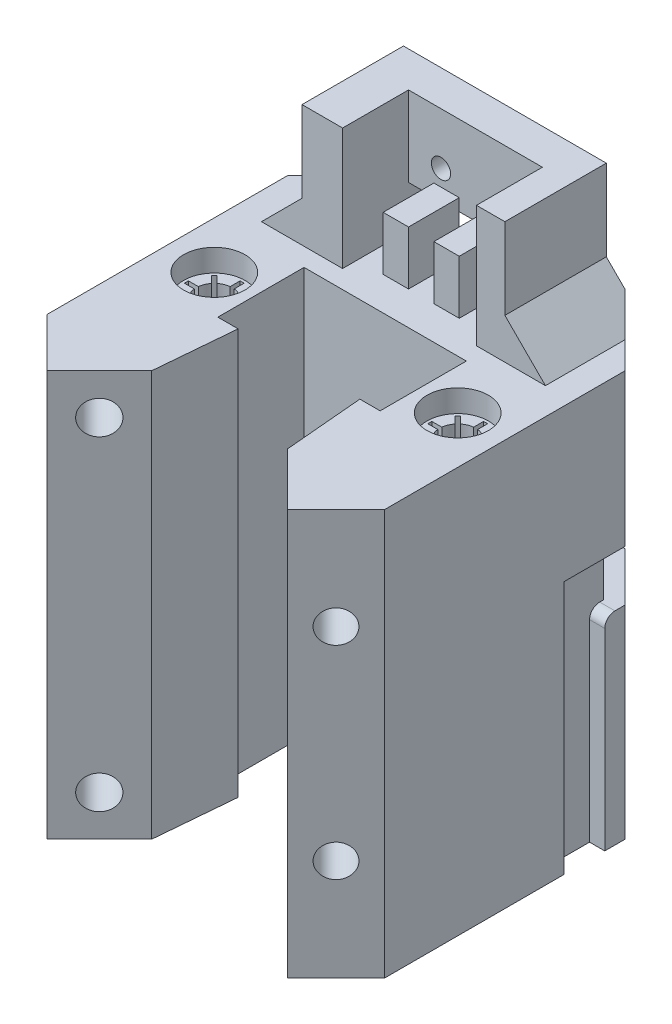
SolidWorks part; units mm, degrees
ref_plane "前视基准面" through (0, 0, 0) normal (0, 0, 1) x (1, 0, 0)
ref_plane "上视基准面" through (0, 0, 0) normal (0, 1, 0) x (1, 0, 0)
ref_plane "右视基准面" through (0, 0, 0) normal (1, 0, 0) x (0, 0, -1)
sketch "草图1" plane through (0, 0, 0) normal (0, 1, 0) x (1, 0, 0)
  line L0 (0, 0) -> (31, 0) construction
  line L1 (0, 0) -> (24.3952, -24.3952) construction
  line L2 (-31, 12) -> (-31, -12) construction
  line L3 (-32.8805, 15.9099) -> (-15.9099, 32.8805) construction
  line L4 (-24.3952, 24.3952) -> (0, 0) construction
  line L5 (-31, 0) -> (0, 0) construction
  line L6 (-43, 22.7609) -> (-43, -22.7609) construction
  line L7 (-43, 22.7609) -> (-22.7609, 43) construction
  line L8 (-24.3952, 24.3952) -> (-32.8805, 32.8805) construction
  line L9 (-31, 0) -> (-43, 0) construction
  line L10 (22.7609, 43) -> (43, 22.7609) construction
  line L11 (22.7609, 43) -> (-22.7609, 43) construction
  line L12 (43, -22.7609) -> (22.7609, -43) construction
  line L13 (43, -22.7609) -> (43, 22.7609) construction
  line L14 (-22.7609, -43) -> (-43, -22.7609) construction
  line L15 (-22.7609, -43) -> (22.7609, -43) construction
  line L16 (24.0036, 46) -> (-24.0036, 46) construction
  line L17 (-46, 24.0036) -> (-24.0036, 46) construction
  line L18 (-46, 24.0036) -> (-46, -24.0036) construction
  line L19 (-24.0036, -46) -> (-46, -24.0036) construction
  line L20 (-24.0036, -46) -> (24.0036, -46) construction
  line L21 (46, -24.0036) -> (24.0036, -46) construction
  line L22 (46, -24.0036) -> (46, 24.0036) construction
  line L23 (24.0036, 46) -> (46, 24.0036) construction
  line L24 (11.8464, 16.65) -> (-11.8464, 16.65)
  line L25 (-16.65, 11.8464) -> (-11.8464, 16.65)
  line L26 (-16.65, 11.8464) -> (-16.65, -11.8464)
  line L27 (-11.8464, -16.65) -> (-16.65, -11.8464)
  line L28 (-11.8464, -16.65) -> (11.8464, -16.65)
  line L29 (16.65, -11.8464) -> (11.8464, -16.65)
  line L30 (16.65, -11.8464) -> (16.65, 11.8464)
  line L31 (11.8464, 16.65) -> (16.65, 11.8464)
  circle A0 centre (0, 0) radius 15 construction
  circle A1 centre (31, 0) radius 12 construction
  circle A2 centre (24.3952, -24.3952) radius 12 construction
  circle A3 centre (0, -31) radius 12 construction
  circle A4 centre (-24.3952, -24.3952) radius 12 construction
  circle A5 centre (-31, 0) radius 12 construction
  circle A6 centre (-24.3952, 24.3952) radius 12 construction
  circle A7 centre (0, 31) radius 12 construction
  circle A8 centre (24.3952, 24.3952) radius 12 construction
  point P22 (0, 0)
  point P41 (0, 0)
  dimension "D1" = 30
  dimension "D2" = 24
  dimension "D3" = 31
  dimension "D4" = 34.5
  dimension "D5" = 45
  dimension "D8" = 3
  dimension "D9" = 26.35
  dimension "D6" = 4
  dimension "D7" = 4
extrude "凸台-拉伸1" add sketch "草图1" along normal blind 40
sketch "草图2" plane through (0, 40, 0) normal (0, 1, 0) x (1, 0, 0)
  line L0 (0, 0) -> (12, 0) construction
  line L1 (0, 0) -> (0, 18.2008) construction
  circle A0 centre (12, 0) radius 1.7
  circle A1 centre (-12, 0) radius 1.7
  dimension "D1" = 3.4
  dimension "D2" = 24
extrude "切除-拉伸1" cut sketch "草图2" against normal through all
sketch "草图3" plane through (0, 40, 0) normal (0, 1, 0) x (1, 0, 0)
  line L0 (0, 0) -> (0, -22.2905) construction
  line L1 (-6, -3.65) -> (6, -3.65)
  line L2 (6, -3.65) -> (6.6859, -11.4895)
  line L5 (-11.8464, -16.65) -> (11.8464, -16.65) construction
  line L9 (-6, -3.65) -> (-6.6859, -11.4895)
  line L10 (6.6859, -11.4895) -> (11.8464, -16.65)
  line L11 (11.8464, -16.65) -> (-11.8464, -16.65)
  line L12 (-6.6859, -11.4895) -> (-11.8464, -16.65)
  point P7 (0, -16.65)
  point P12 (0, -16.65)
  point P15 (0, -3.65)
  dimension "D1" = 45
  dimension "D2" = 12
  dimension "D3" = 95
  dimension "D4" = 13
extrude "切除-拉伸2" cut sketch "草图3" against normal through all
sketch "草图4" plane through (0, 40, 0) normal (0, 1, 0) x (1, 0, 0)
  line L0 (0, 0) -> (0, 19.1016) construction
  line L1 (11.8464, 16.65) -> (-11.8464, 16.65) construction
  line L2 (-10, 6.65) -> (10, 6.65)
  line L3 (-10, 6.65) -> (-10, 16.65)
  line L4 (-10, 16.65) -> (10, 16.65)
  line L5 (10, 6.65) -> (10, 16.65)
  line L6 (-10, 6.65) -> (10, 16.65) construction
  line L7 (-10, 16.65) -> (10, 6.65) construction
  line L9 (-6, 6.65) -> (7.2, 6.65)
  line L10 (-6, 6.65) -> (-6, 13.15)
  line L11 (-6, 13.15) -> (7.2, 13.15)
  line L12 (7.2, 6.65) -> (7.2, 13.15)
  point P3 (0, 11.65)
  line M13 (11.8464, 16.65) -> (-11.8464, 16.65)
  dimension "D1" = 20
  dimension "D2" = 10
  dimension "D3" = 3.5
  dimension "D4" = 13.2
  dimension "D5" = 4
extrude "凸台-拉伸2" add sketch "草图4" along normal blind 12 contours L12 L2 L5 L3 L10 L11 M13
sketch "草图5" plane through (0, 40, 0) normal (0, 1, 0) x (1, 0, 0)
  line L0 (0, 0) -> (0, 7.6634) construction
  line L1 (6, -3.65) -> (-6, -3.65) construction
  line L2 (-6, 4.85) -> (6, 4.85)
  line L3 (-6, 4.85) -> (-6, -3.65)
  line L4 (-6, -3.65) -> (6, -3.65)
  line L5 (6, 4.85) -> (6, -3.65)
  line L6 (-6, 4.85) -> (6, -3.65) construction
  line L7 (-6, -3.65) -> (6, 4.85) construction
  point P3 (0, 0.6)
  dimension "D1" = 12
  dimension "D2" = 8.5
extrude "切除-拉伸3" cut sketch "草图5" against normal through all
sketch "草图6" plane through (0, 0, 0) normal (0, -1, 0) x (1, 0, 0)
  line L0 (-6, -13.15) -> (7.2, -13.15) construction
  line L1 (-6, -13.15) -> (7.2, -13.15) construction
  line L2 (-6, -6.65) -> (-6, -13.15) construction
  line L3 (-6, -6.65) -> (-6, -13.15)
  line L4 (7.2, -6.65) -> (7.2, -13.15) construction
  line L5 (7.2, -6.65) -> (7.2, -13.15)
  line L6 (-6, -6.65) -> (-6, -4.85) construction
  line L7 (-6, -4.85) -> (6, -4.85) construction
  line L8 (6, -4.85) -> (7.2, -6.65) construction
  line L9 (-6, -6.65) -> (7.2, -6.65)
  line L10 (-6, -13.15) -> (-6, -16.65)
  line L11 (11.8464, -16.65) -> (-11.8464, -16.65) construction
  line L12 (-6, -16.65) -> (7.2, -16.65)
  line L13 (7.2, -16.65) -> (7.2, -13.15)
extrude "切除-拉伸4" cut sketch "草图6" against normal blind 12
sketch "草图7" plane through (0, 40, 0) normal (0, 1, 0) x (1, 0, 0)
  line L0 (-6, 13.15) -> (7.2, 13.15) construction
  line L1 (4, 13.15) -> (1.5, 13.15)
  line L2 (4, 13.15) -> (4, 8.15)
  line L3 (4, 8.15) -> (1.5, 8.15)
  line L4 (1.5, 13.15) -> (1.5, 8.15)
  line L6 (-1, 13.15) -> (-3.5, 13.15)
  line L7 (-1, 13.15) -> (-1, 8.15)
  line L8 (-1, 8.15) -> (-3.5, 8.15)
  line L9 (-3.5, 13.15) -> (-3.5, 8.15)
  line L10 (-6, 6.65) -> (-6, 13.15) construction
  dimension "D1" = 2.5
  dimension "D2" = 2.5
  dimension "D3" = 2.5
  dimension "D4" = 5
extrude "凸台-拉伸3" add sketch "草图7" along normal blind 5.3
sketch "草图8" plane through (0, 12, 0) normal (0, -1, 0) x (1, 0, 0)
  line L1 (-3.5, -11.65) -> (-1, -11.65)
  line L2 (-3.5, -11.65) -> (-3.5, -6.65)
  line L3 (-3.5, -6.65) -> (-1, -6.65)
  line L4 (-1, -11.65) -> (-1, -6.65)
  line L5 (-6, -6.65) -> (-6, -16.65) construction
  line L6 (1.5, -11.65) -> (4, -11.65)
  line L7 (1.5, -11.65) -> (1.5, -6.65)
  line L8 (1.5, -6.65) -> (4, -6.65)
  line L9 (4, -11.65) -> (4, -6.65)
  line L10 (7.2, -6.65) -> (-6, -6.65) construction
  dimension "D1" = 2.5
  dimension "D2" = 2.5
  dimension "D3" = 2.5
  dimension "D4" = 5
extrude "凸台-拉伸4" add sketch "草图8" along normal blind 5.2
sketch "草图10" plane through (0, 40, 0) normal (0, 1, 0) x (1, 0, 0)
  line L0 (6, 0.6) -> (-6, 0.6) construction
  line L1 (6, -3.65) -> (6, 4.85) construction
  line L2 (-6, 4.85) -> (-6, -3.65) construction
  line L3 (6, 4.85) -> (-6, 4.85) construction
  line L4 (-8, -3.65) -> (8, -3.65)
  line L5 (-8, -3.65) -> (-8, 4.85)
  line L6 (-8, 4.85) -> (8, 4.85)
  line L7 (8, -3.65) -> (8, 4.85)
  line L8 (-8, -3.65) -> (8, 4.85) construction
  line L9 (-8, 4.85) -> (8, -3.65) construction
  line L10 (-8, 0.6) -> (8, 0.6) construction
  point P6 (0, 0.6)
  dimension "D1" = 16
extrude "切除-拉伸5" cut sketch "草图10" against normal through all
sketch "草图11" plane through (0, 0, -13.15) normal (0, 0, 1) x (1, 0, 0)
  line L1 (-6, 52) -> (-6, 40) construction
  line L2 (1.5, 45.3) -> (-6, 45.3)
  line L3 (1.5, 45.3) -> (1.5, 40)
  line L4 (1.5, 40) -> (-6, 40)
  line L5 (-6, 45.3) -> (-6, 40)
  line L6 (-6, 44.1) -> (1.5, 44.1)
  dimension "D1" = 1.2
extrude "切除-拉伸6" cut sketch "草图11" against normal blind 11
sketch "草图15" plane through (0, 0, -16.65) normal (0, 0, -1) x (-1, 0, 0)
  line L0 (-1.5, 6.8) -> (-1.5, 12) construction
  line L1 (-1.5, 6.8) -> (-1.5, 12) construction
  line L2 (6, 12) -> (6, 0) construction
  line L3 (6, 12) -> (6, 0) construction
  line L5 (-1.5, 12) -> (6, 12)
  line L6 (-1.5, 12) -> (-1.5, 17)
  line L7 (-1.5, 17) -> (6, 17)
  line L8 (6, 12) -> (6, 17)
  dimension "D1" = 5
extrude "切除-拉伸10" cut sketch "草图15" against normal up to surface (10 mm away) up to face at (0.3667, 8.2667, -6.65)
sketch "草图12" plane through (0, 40, 0) normal (0, 1, 0) x (1, 0, 0)
  line L0 (-6, 6.65) -> (-6, 16.65) construction
  line L1 (1.5, 16.65) -> (-6, 16.65)
  line L2 (1.5, 16.65) -> (1.5, 15.15)
  line L3 (1.5, 15.15) -> (-6, 15.15)
  line L4 (-6, 16.65) -> (-6, 15.15)
  dimension "D1" = 1.5
extrude "切除-拉伸7" cut sketch "草图12" against normal up to surface (28 mm away) up to face at (4.2333, 12, -11.65)
sketch "草图13" plane through (0, 0, 0) normal (0, -1, 0) x (1, 0, 0)
  line L0 (11.8464, -16.65) -> (1.5, -16.65)
  line L1 (1.5, -16.65) -> (7.2, -16.65) construction
  line L18 (1.5, -16.65) -> (7.2, -16.65) construction
  line L19 (11.8464, -16.65) -> (16.65, -11.8464)
  line L20 (16.65, -11.8464) -> (16.65, -5.8464)
  line L21 (16.65, 11.8464) -> (16.65, -11.8464) construction
  line L22 (15.15, -11.2251) -> (15.15, -5.8464)
  line L23 (11.2251, -15.15) -> (15.15, -11.2251)
  line L24 (11.2251, -15.15) -> (1.5, -15.15)
  line L25 (16.65, -5.8464) -> (15.15, -5.8464)
  line L26 (1.5, -16.65) -> (1.5, -15.15)
  dimension "D1" = 6
  dimension "D2" = 1.5
extrude "切除-拉伸8" cut sketch "草图13" against normal blind 5 from offset 20 offset against normal yes
fillet "圆角2" radius 2 1 edges at (-2.25, 17, -15.15)
sketch "草图16" plane through (0, 40, 0) normal (0, 1, 0) x (1, 0, 0)
  circle A0 centre (12, 0) radius 3.025
  circle A1 centre (-12, 0) radius 3.025
  dimension "D1" = 6.05
extrude "切除-拉伸11" cut sketch "草图16" against normal blind 2.2
sketch "草图19" plane through (0, 37.8, 0) normal (0, 1, 0) x (1, 0, 0)
  circle A0 centre (-12, 0) radius 1.7 construction
  circle A1 centre (-12, 0) radius 1.7 construction
  circle A2 centre (12, 0) radius 1.7 construction
  circle A3 centre (12, 0) radius 1.7 construction
  line B0 (-10.1969, 2.086) -> (-10.8907, 1.3921)
  line B1 (-12.2, 2.75) -> (-12.2, 1.7687)
  line B2 (-12.2, 2.75) -> (-11.8, 2.75)
  line B3 (-11.8, 2.75) -> (-11.8, 1.7687)
  line B4 (-9.914, 1.8031) -> (-10.6079, 1.1093)
  line B5 (-10.1969, 2.086) -> (-9.914, 1.8031)
  line B6 (-9.25, 0.2) -> (-10.2313, 0.2)
  line B7 (-9.25, -0.2) -> (-10.2313, -0.2)
  line B8 (-9.25, 0.2) -> (-9.25, -0.2)
  line B9 (-9.914, -1.8031) -> (-10.6079, -1.1093)
  line B10 (-10.1969, -2.086) -> (-10.8907, -1.3921)
  line B11 (-9.914, -1.8031) -> (-10.1969, -2.086)
  line B12 (-11.8, -2.75) -> (-11.8, -1.7687)
  line B13 (-12.2, -2.75) -> (-12.2, -1.7687)
  line B14 (-11.8, -2.75) -> (-12.2, -2.75)
  line B15 (-13.8031, -2.086) -> (-13.1093, -1.3921)
  line B16 (-14.086, -1.8031) -> (-13.3921, -1.1093)
  line B17 (-13.8031, -2.086) -> (-14.086, -1.8031)
  line B18 (-14.75, -0.2) -> (-13.7687, -0.2)
  line B19 (-14.75, 0.2) -> (-13.7687, 0.2)
  line B20 (-14.75, -0.2) -> (-14.75, 0.2)
  line B21 (-14.086, 1.8031) -> (-13.3921, 1.1093)
  line B22 (-13.8031, 2.086) -> (-13.1093, 1.3921)
  line B23 (-14.086, 1.8031) -> (-13.8031, 2.086)
  arc B24 (-12.2, 1.7687) -> (-13.1093, 1.3921) centre (-12, 0) ccw
  arc B25 (-10.8907, 1.3921) -> (-11.8, 1.7687) centre (-12, 0) ccw
  arc B26 (-10.6079, -1.1093) -> (-10.2313, -0.2) centre (-12, 0) ccw
  arc B27 (-11.8, -1.7687) -> (-10.8907, -1.3921) centre (-12, 0) ccw
  arc B28 (-13.1093, -1.3921) -> (-12.2, -1.7687) centre (-12, 0) ccw
  arc B29 (-13.7687, -0.2) -> (-13.3921, -1.1093) centre (-12, 0) ccw
  arc B30 (-13.3921, 1.1093) -> (-13.7687, 0.2) centre (-12, 0) ccw
  arc B31 (-10.2313, 0.2) -> (-10.6079, 1.1093) centre (-12, 0) ccw
  line B32 (13.8031, 2.086) -> (13.1093, 1.3921)
  line B33 (11.8, 2.75) -> (11.8, 1.7687)
  line B34 (11.8, 2.75) -> (12.2, 2.75)
  line B35 (12.2, 2.75) -> (12.2, 1.7687)
  line B36 (14.086, 1.8031) -> (13.3921, 1.1093)
  line B37 (13.8031, 2.086) -> (14.086, 1.8031)
  line B38 (14.75, 0.2) -> (13.7687, 0.2)
  line B39 (14.75, -0.2) -> (13.7687, -0.2)
  line B40 (14.75, 0.2) -> (14.75, -0.2)
  line B41 (14.086, -1.8031) -> (13.3921, -1.1093)
  line B42 (13.8031, -2.086) -> (13.1093, -1.3921)
  line B43 (14.086, -1.8031) -> (13.8031, -2.086)
  line B44 (12.2, -2.75) -> (12.2, -1.7687)
  line B45 (11.8, -2.75) -> (11.8, -1.7687)
  line B46 (12.2, -2.75) -> (11.8, -2.75)
  line B47 (10.1969, -2.086) -> (10.8907, -1.3921)
  line B48 (9.914, -1.8031) -> (10.6079, -1.1093)
  line B49 (10.1969, -2.086) -> (9.914, -1.8031)
  line B50 (9.25, -0.2) -> (10.2313, -0.2)
  line B51 (9.25, 0.2) -> (10.2313, 0.2)
  line B52 (9.25, -0.2) -> (9.25, 0.2)
  line B53 (9.914, 1.8031) -> (10.6079, 1.1093)
  line B54 (10.1969, 2.086) -> (10.8907, 1.3921)
  line B55 (9.914, 1.8031) -> (10.1969, 2.086)
  arc B56 (11.8, 1.7687) -> (10.8907, 1.3921) centre (12, 0) ccw
  arc B57 (13.1093, 1.3921) -> (12.2, 1.7687) centre (12, 0) ccw
  arc B58 (13.3921, -1.1093) -> (13.7687, -0.2) centre (12, 0) ccw
  arc B59 (12.2, -1.7687) -> (13.1093, -1.3921) centre (12, 0) ccw
  arc B60 (10.8907, -1.3921) -> (11.8, -1.7687) centre (12, 0) ccw
  arc B61 (10.2313, -0.2) -> (10.6079, -1.1093) centre (12, 0) ccw
  arc B62 (10.6079, 1.1093) -> (10.2313, 0.2) centre (12, 0) ccw
  arc B63 (13.7687, 0.2) -> (13.3921, 1.1093) centre (12, 0) ccw
sketch_block_instance "块1-1"
sketch_block "块1" parameters "D1"=3.56, "D2"=0.4, "D3"=2.75
sketch_block_instance "块1-2"
sketch_block "块1" parameters "D1"=3.56, "D2"=0.4, "D3"=2.75
extrude "切除-拉伸13" cut sketch "草图19" against normal blind 2.8
ref_plane "基准面1" through (0, 20, 0) normal (0, 1, 0) x (1, 0, 0)
mirror "镜向1" about plane through (0, 20, 0) normal (0, 1, 0) of "切除-拉伸13", "切除-拉伸11"
sketch "草图21" plane through (-14.2482, 0, 14.2482) normal (-0.7071, 0, 0.7071) x (0.7071, 0, 0.7071)
  line L0 (0, 0) -> (0, 40) construction
  line L2 (0, 20) -> (14.1722, 20) construction
  line L3 (-3.3967, 40) -> (3.3967, 40) construction
  line L4 (-3.3967, 0) -> (3.3967, 0) construction
  circle A0 centre (0, 30) radius 1.6
  circle A2 centre (0, 10) radius 1.6
  point P17 (0, 0)
  dimension "D1" = 3.2
  dimension "D2" = 20
  dimension "D3" = 0
extrude "切除-拉伸14" cut sketch "草图21" against normal blind 5
chamfer "倒角1" [suppressed] distance 1 angle 45
mirror "镜向2" about plane through (0, 0, 0) normal (1, 0, 0) of "切除-拉伸14"
mirror "镜向3" about plane through (0, 0, 0) normal (0, 0, 1) of "镜向2", "切除-拉伸14"
sketch "草图17" plane through (0, 20, 0) normal (0, 1, 0) x (1, 0, 0)
  line L5 (15.15, 5.8464) -> (15.15, 11.2251) construction
  line L6 (16.65, 5.8464) -> (15.15, 5.8464)
  line L7 (16.65, 5.8464) -> (16.65, 9.8464)
  line L8 (16.65, 9.8464) -> (15.15, 9.8464)
  line L9 (15.15, 5.8464) -> (15.15, 9.8464)
  dimension "D1" = 4
extrude "切除-拉伸12" cut sketch "草图17" against normal through all
fillet "圆角3" radius 1 3 edges at (15.9, 20, -9.8464) (1.5, 20, -15.9) (1.5, 25, -15.9)
chamfer "倒角2" distance 4 angle 45 2 edges at (10, 40, -11.65) (-10, 40, -11.65)
sketch "草图22" plane through (0, 0, -13.15) normal (0, 0, 1) x (1, 0, 0)
  line L0 (-2.8, 46.9) -> (3.7, 46.9) construction
  line L1 (-6, 52) -> (-6, 40) construction
  line L2 (-6, 52) -> (7.2, 52) construction
  circle A0 centre (-2.8, 46.9) radius 0.95
  circle A1 centre (3.7, 46.9) radius 0.95
  dimension "D1" = 1.9
  dimension "D2" = 6.5
  dimension "D3" = 3.2
  dimension "D4" = 5.1
extrude "切除-拉伸15" cut sketch "草图22" against normal through all
sketch "草图23" plane through (0, 0, -6.65) normal (0, 0, -1) x (-1, 0, 0)
  line L0 (2.8, 5.1) -> (-3.7, 5.1) construction
  line L1 (6, 17) -> (6, 0) construction
  line L2 (-7.2, 0) -> (6, 0) construction
  circle A0 centre (2.8, 5.1) radius 0.95
  circle A1 centre (-3.7, 5.1) radius 0.95
  dimension "D1" = 1.9
  dimension "D2" = 6.5
  dimension "D3" = 3.2
  dimension "D4" = 5.1
extrude "切除-拉伸16" cut sketch "草图23" against normal through all
sketch "草图25" plane through (2.4018, 0, 2.4018) normal (0.7071, 0, 0.7071) x (0.7071, 0, -0.7071)
  line L0 (-16.5009, 40) -> (-16.5009, 0) construction
  line L1 (-12.8519, 40) -> (-20.15, 40) construction
  line L2 (-12.8519, 0) -> (-20.15, 0) construction
  line L3 (-16.5009, 20) -> (-32.9104, 20) construction
  circle A0 centre (-16.5009, 36) radius 1.65
  circle A1 centre (-16.5009, 4) radius 1.65
  dimension "D1" = 3.3
  dimension "D2" = 4
extrude "切除-拉伸17" cut sketch "草图25" against normal blind 5
mirror "镜向4" about plane through (0, 0, 0) normal (1, 0, 0) of "切除-拉伸17"
